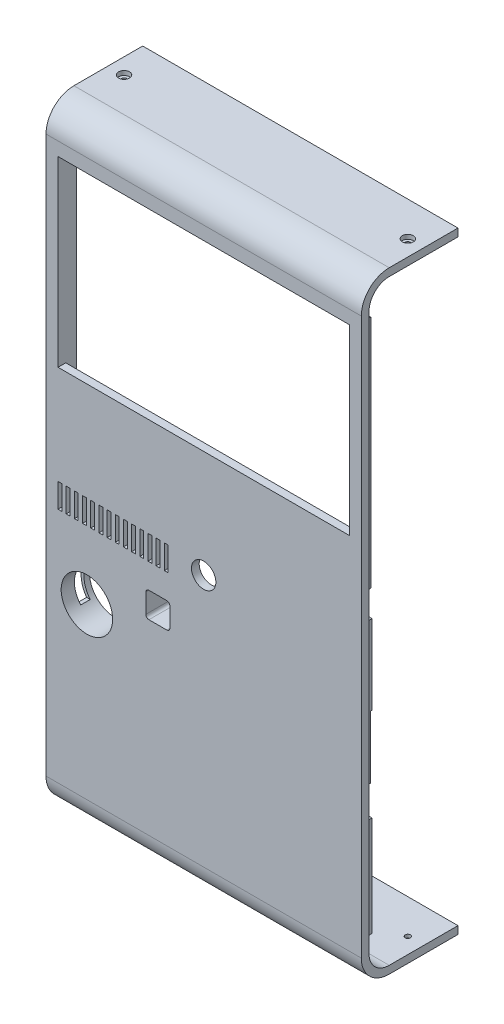
SolidWorks part; units mm, degrees
ref_plane "Alzado" through (0, 0, 0) normal (0, 0, 1) x (1, 0, 0)
ref_plane "Planta" through (0, 0, 0) normal (0, 1, 0) x (1, 0, 0)
ref_plane "Vista lateral" through (0, 0, 0) normal (1, 0, 0) x (0, 0, -1)
sketch "Croquis2" plane through (0, 0, 0) normal (1, 0, 0) x (0, 0, -1)
  line L0 (37, 0) -> (37, -3.2)
  line L1 (8.4, 0) -> (37, 0)
  line L2 (0, 8.4) -> (0, 239.6)
  line L3 (8.4, 248) -> (37, 248)
  line L5 (37, 248) -> (37, 251.2)
  line L6 (37, -3.2) -> (8.4, -3.2)
  line L7 (37, 251.2) -> (8.4, 251.2)
  line L8 (-3.2, 239.6) -> (-3.2, 8.4)
  arc A0 (8.4, 248) -> (0, 239.6) centre (8.4, 239.6) ccw
  arc A1 (0, 8.4) -> (8.4, 0) centre (8.4, 8.4) ccw
  arc A4 (8.4, 251.2) -> (-3.2, 239.6) centre (8.4, 239.6) ccw
  arc A5 (-3.2, 8.4) -> (8.4, -3.2) centre (8.4, 8.4) ccw
  point P9 (0, 0)
  dimension "D3" = 8.4
  dimension "D6" = 3.2
  dimension "D5" = 11.6
  dimension "D1" = 248
  dimension "D2" = 37
  dimension "D4" = 3.2
extrude "Saliente-Extruir1" add sketch "Croquis2" along normal blind 131.1
sketch "Croquis3" plane through (0, 251.2, 0) normal (0, 1, 0) x (1, 0, 0)
  line L0 (131.1, 37) -> (0, 37) construction
  line L1 (0, 37) -> (0, 8.4) construction
  line L2 (65.55, 37) -> (65.55, 8.4) construction
  line L4 (131.1, 8.4) -> (0, 8.4) construction
  circle A0 centre (6.55, 22.7) radius 1.1
  circle A1 centre (124.55, 22.7) radius 1.1
  dimension "D3" = 2.2
  dimension "D1" = 14.3
  dimension "D2" = 6.55
extrude "Cortar-Extruir1" cut sketch "Croquis3" against normal through all
sketch "Croquis4" plane through (0, 0, 3.2) normal (0, 0, 1) x (1, 0, 0)
  line L0 (131.1, 8.4) -> (0, 8.4) construction
  line L1 (0, 249.9) -> (0, 248) construction
  line L2 (65.55, 239.6) -> (65.55, 8.4) construction
  line L4 (5, 234) -> (126.1, 234)
  line L5 (126.1, 234) -> (126.1, 158.2)
  line L6 (126.1, 158.2) -> (5, 158.2)
  line L7 (5, 158.2) -> (5, 234)
  line L8 (0, 239.6) -> (0, 8.4) construction
  line L9 (131.1, 239.6) -> (0, 239.6) construction
  line L10 (8.4, 117) -> (8.4, 107)
  line L11 (41.5, 86.1) -> (51.5, 86.1)
  line L12 (41.5, 86.1) -> (41.5, 96.7)
  line L13 (41.5, 96.7) -> (51.5, 96.7)
  line L14 (51.5, 86.1) -> (51.5, 96.7)
  line L15 (5, 117) -> (6.6, 117)
  line L16 (5, 117) -> (5, 107)
  line L17 (5, 107) -> (6.6, 107)
  line L18 (6.6, 117) -> (6.6, 107)
  line L19 (8.4, 117) -> (10, 117)
  line L20 (10, 117) -> (10, 107)
  line L21 (8.4, 107) -> (10, 107)
  line L22 (11.8, 117) -> (11.8, 107)
  line L23 (11.8, 117) -> (13.4, 117)
  line L24 (13.4, 117) -> (13.4, 107)
  line L25 (11.8, 107) -> (13.4, 107)
  line L26 (15.2, 117) -> (15.2, 107)
  line L27 (15.2, 117) -> (16.8, 117)
  line L28 (16.8, 117) -> (16.8, 107)
  line L29 (15.2, 107) -> (16.8, 107)
  line L30 (18.6, 117) -> (18.6, 107)
  line L31 (18.6, 117) -> (20.2, 117)
  line L32 (20.2, 117) -> (20.2, 107)
  line L33 (18.6, 107) -> (20.2, 107)
  line L34 (22, 117) -> (22, 107)
  line L35 (22, 117) -> (23.6, 117)
  line L36 (23.6, 117) -> (23.6, 107)
  line L37 (22, 107) -> (23.6, 107)
  line L38 (25.4, 117) -> (25.4, 107)
  line L39 (25.4, 117) -> (27, 117)
  line L40 (27, 117) -> (27, 107)
  line L41 (25.4, 107) -> (27, 107)
  line L42 (28.8, 117) -> (28.8, 107)
  line L43 (28.8, 117) -> (30.4, 117)
  line L44 (30.4, 117) -> (30.4, 107)
  line L45 (28.8, 107) -> (30.4, 107)
  line L46 (32.2, 117) -> (32.2, 107)
  line L47 (32.2, 117) -> (33.8, 117)
  line L48 (33.8, 117) -> (33.8, 107)
  line L49 (32.2, 107) -> (33.8, 107)
  line L50 (35.6, 117) -> (35.6, 107)
  line L51 (35.6, 117) -> (37.2, 117)
  line L52 (37.2, 117) -> (37.2, 107)
  line L53 (35.6, 107) -> (37.2, 107)
  line L54 (39, 117) -> (39, 107)
  line L55 (39, 117) -> (40.6, 117)
  line L56 (40.6, 117) -> (40.6, 107)
  line L57 (39, 107) -> (40.6, 107)
  line L58 (42.4, 117) -> (42.4, 107)
  line L59 (42.4, 117) -> (44, 117)
  line L60 (44, 117) -> (44, 107)
  line L61 (42.4, 107) -> (44, 107)
  line L62 (45.8, 117) -> (45.8, 107)
  line L63 (45.8, 117) -> (47.4, 117)
  line L64 (47.4, 117) -> (47.4, 107)
  line L65 (45.8, 107) -> (47.4, 107)
  line L66 (49.2, 117) -> (49.2, 107)
  line L67 (49.2, 117) -> (50.8, 117)
  line L68 (50.8, 117) -> (50.8, 107)
  line L69 (49.2, 107) -> (50.8, 107)
  circle A0 centre (17, 78.7) radius 10.7
  circle A1 centre (65.55, 113.5) radius 5.07
  point P0 (5, 234)
  point P9 (126.1, 234)
  dimension "D6" = 21.4
  dimension "D16" = 10.14
  dimension "D2" = 121.1
  dimension "D3" = 75.8
  dimension "D4" = 17
  dimension "D5" = 169.3
  dimension "D7" = 24.5
  dimension "D8" = 151.3
  dimension "D9" = 10
  dimension "D10" = 10.6
  dimension "D11" = 131
  dimension "D12" = 10
  dimension "D13" = 1.6
  dimension "D14" = 5
  dimension "D17" = 134.5
  dimension "D18" = 14
  dimension "D15" = 14
extrude "Cortar-Extruir2" cut sketch "Croquis4" against normal through all
sketch "Croquis7" plane through (0, 0, 0) normal (0, 0, -1) x (-1, 0, 0)
  line L5 (-127.46, 125.3) -> (-127.96, 125.3)
  line L10 (-126.1, 234) -> (-127.46, 234)
  line L11 (-126.1, 234) -> (-126.1, 136)
  line L12 (-126.1, 136) -> (-127.46, 136)
  line L13 (-127.46, 234) -> (-127.46, 136)
  line L14 (-5, 234) -> (-3.64, 234)
  line L15 (-5, 234) -> (-5, 136)
  line L16 (-5, 136) -> (-3.64, 136)
  line L17 (-3.64, 234) -> (-3.64, 136)
  line L18 (-127.46, 125.3) -> (-126.1, 125.3)
  line L20 (-127.46, 66.3) -> (-126.1, 66.3)
  line L21 (-126.1, 125.3) -> (-126.1, 66.3)
  line L22 (-3.64, 125.3) -> (-5, 125.3)
  line L24 (-3.64, 66.3) -> (-5, 66.3)
  line L25 (-5, 125.3) -> (-5, 66.3)
  line L27 (-127.46, 66.3) -> (-127.96, 66.3)
  line L28 (-127.96, 125.3) -> (-127.96, 66.3)
  line L29 (-3.64, 125.3) -> (-3.14, 125.3)
  line L31 (-3.64, 66.3) -> (-3.14, 66.3)
  line L32 (-3.14, 125.3) -> (-3.14, 66.3)
  line L33 (-126.1, 53.5) -> (-127.96, 53.5)
  line L34 (-126.1, 53.5) -> (-126.1, 11.9)
  line L35 (-126.1, 11.9) -> (-127.96, 11.9)
  line L36 (-127.96, 53.5) -> (-127.96, 11.9)
  line L37 (-5, 53.5) -> (-3.14, 53.5)
  line L38 (-5, 53.5) -> (-5, 11.9)
  line L39 (-5, 11.9) -> (-3.14, 11.9)
  line L40 (-3.14, 53.5) -> (-3.14, 11.9)
  dimension "D1" = 1.36
  dimension "D2" = 98
  dimension "D3" = 10.7
  dimension "D4" = 59
  dimension "D5" = 0.5
  dimension "D6" = 0.5
  dimension "D7" = 12.8
  dimension "D8" = 1.36
  dimension "D9" = 1.36
  dimension "D10" = 0.5
  dimension "D11" = 1.36
  dimension "D12" = 41.6
extrude "Saliente-Extruir2" add sketch "Croquis7" along normal blind 4.4
sketch "Croquis8" plane through (0, 251.2, 0) normal (0, 1, 0) x (1, 0, 0)
  circle A0 centre (6.55, 22.7) radius 2.27
  circle A1 centre (124.55, 22.7) radius 2.27
  dimension "D1" = 4.54
extrude "Cortar-Extruir3" cut sketch "Croquis8" against normal blind 1.8
sketch "Croquis9" plane through (0, -3.2, 0) normal (0, -1, 0) x (1, 0, 0)
  circle A0 centre (124.55, -22.7) radius 2.27
  circle A1 centre (6.55, -22.7) radius 2.27
  dimension "D1" = 4.54
extrude "Cortar-Extruir4" cut sketch "Croquis9" against normal blind 1.8
sketch "Croquis10" plane through (0, 0, 0) normal (0, 0, -1) x (-1, 0, 0)
  line L0 (-41.5, 86.1) -> (-51.5, 86.1) construction
  line L1 (-51.5, 96.7) -> (-41.5, 96.7)
  line L2 (-51.5, 96.7) -> (-51.5, 86.1)
  line L3 (-51.5, 86.1) -> (-41.5, 86.1)
  line L4 (-41.5, 96.7) -> (-41.5, 86.1)
  line L5 (-52.7, 97.9) -> (-40.3, 97.9)
  line L6 (-40.3, 97.9) -> (-40.3, 84.9)
  line L7 (-40.3, 84.9) -> (-52.7, 84.9)
  line L8 (-52.7, 84.9) -> (-52.7, 97.9)
  line L9 (-41.5, 96.7) -> (-41.5, 86.1) construction
  circle A0 centre (-17, 78.7) radius 11.9
  circle A1 centre (-17, 78.7) radius 10.7 construction
  circle A2 centre (-17, 78.7) radius 10.7
  dimension "D1" = 1.2
  dimension "D2" = 1.2
  dimension "D3" = 1.2
  dimension "D4" = 1.2
  dimension "D5" = 1.2
extrude "Saliente-Extruir4" add sketch "Croquis10" along normal blind 8.6
fillet "Redondeo2" radius 1.28 4 edges at (51.5, 86.1, -2.7) (51.5, 96.7, -2.7) (41.5, 96.7, -2.7) (41.5, 86.1, -2.7)
ref_plane "Plano1" through (-10, 0, 0) normal (-1, 0, 0) x (0, 0, 1)
sketch "Croquis11" plane through (-10, 0, 0) normal (-1, 0, 0) x (0, 0, 1)
  line L0 (-8.6, 78.7) -> (0, 78.7) construction
  line L1 (-8.6, 90.6) -> (-8.6, 66.8) construction
  line L4 (-6.3, 71.7) -> (-2.3, 71.7)
  line L5 (-6.3, 71.7) -> (-6.3, 85.7)
  line L6 (-6.3, 85.7) -> (-2.3, 85.7)
  line L7 (-2.3, 71.7) -> (-2.3, 85.7)
  line L8 (-6.3, 71.7) -> (-2.3, 85.7) construction
  line L9 (-6.3, 85.7) -> (-2.3, 71.7) construction
  line L10 (0, 8.4) -> (0, 239.6) construction
  point P6 (-4.3, 78.7)
  dimension "D1" = 4
  dimension "D2" = 14
extrude "Cortar-Extruir5" cut sketch "Croquis11" against normal up to surface (18.9074 mm away)
sketch "Croquis13" plane through (0, 0, -8.6) normal (0, 0, -1) x (-1, 0, 0)
  line L0 (-50.22, 96.7) -> (-42.78, 96.7)
  line L1 (-50.22, 86.1) -> (-42.78, 86.1)
  line L2 (-41.5, 87.38) -> (-41.5, 95.42)
  line L3 (-51.5, 87.38) -> (-51.5, 95.42)
  line L4 (-52.7, 97.9) -> (-52.7, 84.9)
  line L5 (-52.7, 84.9) -> (-40.3, 84.9)
  line L6 (-40.3, 84.9) -> (-40.3, 97.9)
  line L7 (-40.3, 97.9) -> (-52.7, 97.9)
  line L8 (-52.7, 97.9) -> (-52.7, 84.9)
  line L9 (-52.7, 84.9) -> (-40.3, 84.9)
  line L10 (-40.3, 84.9) -> (-40.3, 97.9)
  line L11 (-40.3, 97.9) -> (-52.7, 97.9)
  circle A0 centre (-50.22, 95.42) radius 1.28
  circle A1 centre (-50.22, 87.38) radius 1.28
  circle A2 centre (-42.78, 87.38) radius 1.28
  circle A3 centre (-42.78, 95.42) radius 1.28
  line M5 (-52.7, 97.9) -> (-52.7, 84.9)
  line M6 (-52.7, 84.9) -> (-40.3, 84.9)
  line M7 (-40.3, 84.9) -> (-40.3, 97.9)
  line M8 (-40.3, 97.9) -> (-52.7, 97.9)
  line M9 (-51.5, 87.38) -> (-51.5, 95.42)
  arc M10 (-51.5, 95.42) -> (-50.22, 96.7) centre (-50.22, 95.42) cw
  line M11 (-50.22, 96.7) -> (-42.78, 96.7)
  arc M12 (-42.78, 96.7) -> (-41.5, 95.42) centre (-42.78, 95.42) cw
  line M13 (-41.5, 95.42) -> (-41.5, 87.38)
  arc M14 (-41.5, 87.38) -> (-42.78, 86.1) centre (-42.78, 87.38) cw
  line M15 (-42.78, 86.1) -> (-50.22, 86.1)
  arc M16 (-50.22, 86.1) -> (-51.5, 87.38) centre (-50.22, 87.38) cw
  dimension "D1" = 0
extrude "Saliente-Extruir6" add sketch "Croquis13" along normal blind 1 contours M8 M5 M6 M7 M16 M9 M10 M11 M12 M13 M14 M15
sketch "Croquis14" plane through (0, 0, 0) normal (0, 0, -1) x (-1, 0, 0)
  line L0 (-65.55, 113.5) -> (-65.55, 74.9205) construction
  circle A0 centre (-65.55, 88.8) radius 1.5
  circle A1 centre (-65.55, 88.8) radius 2.8
  dimension "D2" = 3
  dimension "D3" = 5.6
  dimension "D1" = 24.7
extrude "Saliente-Extruir7" add sketch "Croquis14" along normal blind 8.4
fillet "Redondeo3" radius 1.28 1 edges at (68.35, 88.8, 0)
sketch "Croquis17" plane through (127.46, 0, 0) normal (1, 0, 0) x (0, 0, -1)
  line L0 (4.4, 234) -> (4.4, 136) construction
  line L1 (0, 234) -> (4.4, 234)
  line L2 (0, 234) -> (0, 233.6)
  line L3 (0, 233.6) -> (4.4, 233.6)
  line L4 (4.4, 234) -> (4.4, 233.6)
  dimension "D1" = 0.4
extrude "Cortar-Extruir6" cut sketch "Croquis17" against normal through all
fillet "Redondeo4" radius 1.6 2 edges at (52.7, 91.4, 0) (40.3, 91.4, 0)
sketch "Croquis19" plane through (0, 0, 0) normal (0, 0, -1) x (-1, 0, 0)
  line L5 (-17, 66.8) -> (-17, 78.7) construction
  line L18 (-17, 78.7) -> (-17, 90.6) construction
  circle A2 centre (-17, 78.7) radius 11.9 construction
  circle A3 centre (-17, 90.6) radius 1.12
  circle A4 centre (-17, 66.8) radius 1.12
  dimension "D1" = 2.24
extrude "Saliente-Extruir8" add sketch "Croquis19" along normal up to surface (8.6 mm away) up to face at (5.1, 78.7, -8.6)
fillet "Redondeo5" radius 1 1 edges at (28.9, 78.7, 0)
sketch "Croquis21" plane through (127.96, 0, 0) normal (1, 0, 0) x (0, 0, -1)
  line L1 (4.4, 66.3) -> (3.8, 66.3)
  line L2 (4.4, 66.3) -> (4.4, 92.3)
  line L3 (4.4, 92.3) -> (3.8, 92.3)
  line L4 (3.8, 66.3) -> (3.8, 92.3)
  dimension "D1" = 0.6
  dimension "D2" = 26
extrude "Cortar-Extruir8" cut sketch "Croquis21" against normal up to vertex
sketch "Croquis23" plane through (0, 0, 3.2) normal (0, 0, 1) x (1, 0, 0)
  line L0 (126.1, 158.2) -> (126.1, 234) construction
  line L1 (5, 158.2) -> (126.1, 158.2)
  line L2 (5, 158.2) -> (5, 158.1)
  line L3 (5, 158.1) -> (126.1, 158.1)
  line L4 (126.1, 158.2) -> (126.1, 158.1)
  dimension "D1" = 0.1
extrude "Cortar-Extruir9" cut sketch "Croquis23" against normal through all
